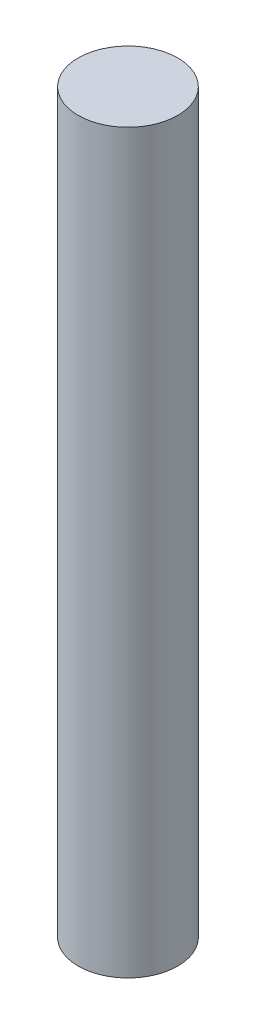
SolidWorks part; units mm, degrees
ref_plane "Front Plane" through (0, 0, 0) normal (0, 0, 1) x (1, 0, 0)
ref_plane "Top Plane" through (0, 0, 0) normal (0, 1, 0) x (1, 0, 0)
ref_plane "Right Plane" through (0, 0, 0) normal (1, 0, 0) x (0, 0, -1)
sketch "Sketch2" plane through (0, 0, 0) normal (0, 1, 0) x (1, 0, 0)
  circle A0 centre (0, 0) radius 2.5
  dimension "D1" = 5
extrude "Boss-Extrude1" add sketch "Sketch2" along normal blind 37
